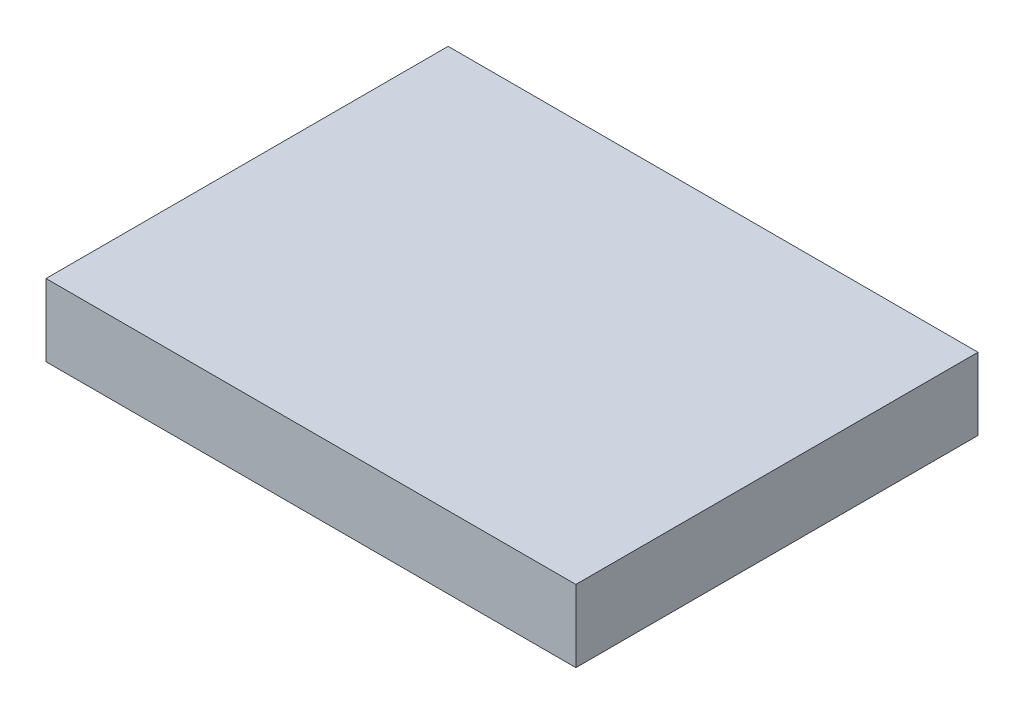
SolidWorks part; units mm, degrees
ref_plane "Front Plane" through (0, 0, 0) normal (0, 0, 1) x (1, 0, 0)
ref_plane "Top Plane" through (0, 0, 0) normal (0, 1, 0) x (1, 0, 0)
ref_plane "Right Plane" through (0, 0, 0) normal (1, 0, 0) x (0, 0, -1)
sketch "Sketch1" plane through (0, 0, 0) normal (0, 1, 0) x (1, 0, 0)
  line L5 (-8.1661, -6.1976) -> (8.1661, -6.1976)
  line L6 (-8.1661, -6.1976) -> (-8.1661, 6.1976)
  line L7 (-8.1661, 6.1976) -> (8.1661, 6.1976)
  line L8 (8.1661, -6.1976) -> (8.1661, 6.1976)
  line L9 (-8.1661, -6.1976) -> (8.1661, 6.1976) construction
  line L10 (-8.1661, 6.1976) -> (8.1661, -6.1976) construction
  point P0 (0, 0)
  dimension "D1" = 16.3322
  dimension "D2" = 12.3952
extrude "Boss-Extrude1" add sketch "Sketch1" along normal blind 2.2225
